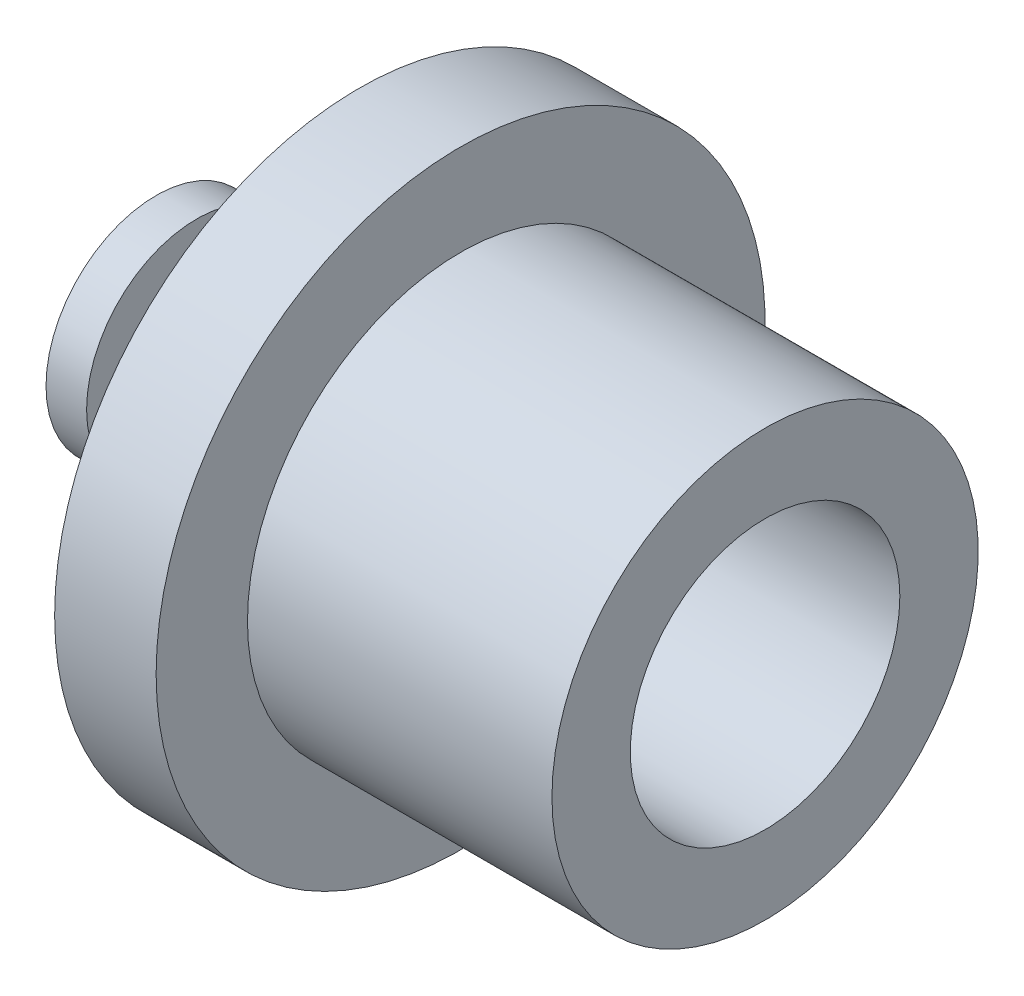
SolidWorks part; units mm, degrees
material "6061-T6 (SS)"
ref_plane "Front Plane" through (0, 0, 0) normal (0, 0, 1) x (1, 0, 0)
ref_plane "Top Plane" through (0, 0, 0) normal (0, 1, 0) x (1, 0, 0)
ref_plane "Right Plane" through (0, 0, 0) normal (1, 0, 0) x (0, 0, -1)
sketch "Sketch1" plane through (0, 0, 0) normal (0, 0, 1) x (1, 0, 0)
  line L0 (0, 0) -> (17.3276, 0) construction
  line L1 (6.35, 3.4449) -> (6.35, 9.525)
  line L2 (6.35, 9.525) -> (9.525, 9.525)
  line L3 (9.525, 9.525) -> (9.525, 6.6675)
  line L4 (9.525, 6.6675) -> (19.05, 6.6675)
  line L5 (19.05, 6.6675) -> (19.05, 0)
  line L6 (19.05, 0) -> (0, 0)
  line L7 (0, 0) -> (0, 3.4449)
  line L8 (0, 3.4449) -> (1.27, 3.4449)
  line L9 (3.81, 3.4449) -> (6.35, 3.4449)
  line L11 (1.27, 3.4449) -> (1.27, 2.0733)
  line L12 (1.27, 2.0733) -> (3.81, 2.0733)
  line L13 (3.81, 3.4449) -> (3.81, 2.0733)
  dimension "D1" = 19.05
  dimension "D2" = 13.335
  dimension "D3" = 3.175
  dimension "D4" = 9.525
  dimension "D5" = 6.8897
  dimension "D6" = 1.3716
  dimension "D7" = 2.54
  dimension "D8" = 1.27
  dimension "D9" = 2.54
revolve "Revolve1" add sketch "Sketch1" angle 360 about L0
hole_wizard "Pipe Tap Drill for 1/8 Tap1" positions "Sketch2" profile "Sketch3" hole size "1/8" standard "ANSI Inch"
sketch "Sketch2" plane through (19.05, 0, 0) normal (1, 0, 0) x (0, 0, -1)
  point P0 (0, 0)
sketch "Sketch3" plane through (19.05, 0, 0) normal (0, 1, 0) x (0, 0, -1)
  line L0 (0, 0) -> (0, 12.0585)
  line L1 (0, 12.0585) -> (4.2164, 9.525)
  line L2 (4.2164, 9.525) -> (4.2164, 0)
  line L5 (4.2164, 0) -> (0, 0)
  line L10 (0, 12.0585) -> (-4.2164, 9.525) construction
  line L11 (0, -6.35) -> (0, 107.95) construction
  dimension "Hole Dia." = 8.4328
  dimension "Hole Depth" = 9.525
  dimension "Drill Angle" = 118
hole_wizard "3/32 (0.09375) Diameter Hole2" positions "Sketch4" profile "Sketch5" hole size "3/32" standard "ANSI Inch"
sketch "Sketch4" plane through (0, 0, 0) normal (-1, 0, 0) x (0, 0, 1)
  point P0 (0, 0)
sketch "Sketch5" plane through (0, 0, 0) normal (0, 1, 0) x (0, 0, 1)
  line L0 (0, 0) -> (0, 13.4154)
  line L1 (0, 13.4154) -> (1.1906, 12.7)
  line L2 (1.1906, 12.7) -> (1.1906, 0)
  line L5 (1.1906, 0) -> (0, 0)
  line L10 (0, 13.4154) -> (-1.1906, 12.7) construction
  line L11 (0, -6.35) -> (0, 107.95) construction
  dimension "Hole Dia." = 2.3812
  dimension "Hole Depth" = 12.7
  dimension "Drill Angle" = 118
